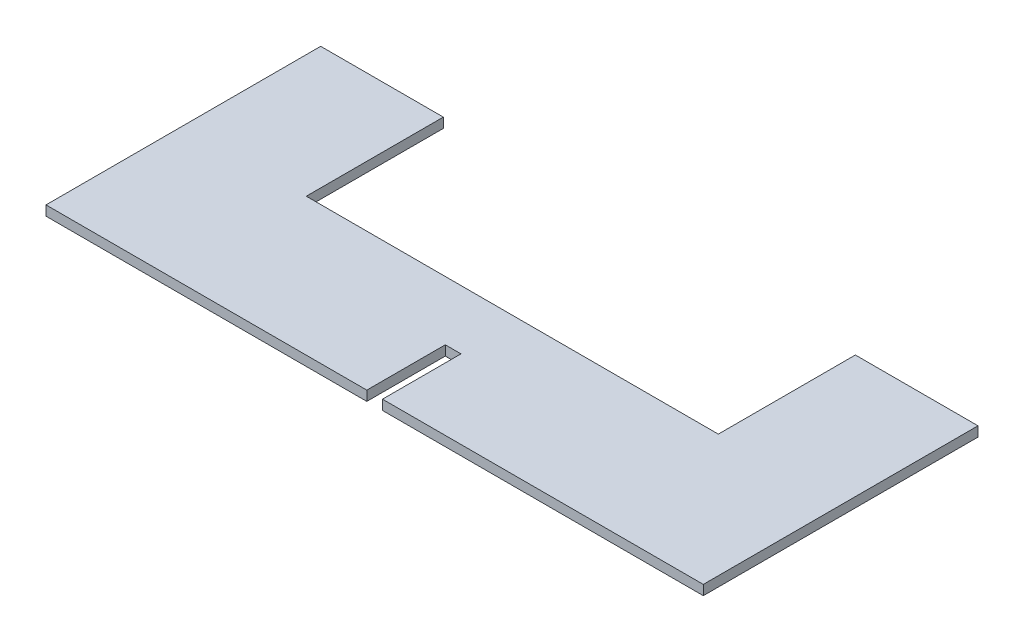
SolidWorks part; units mm, degrees
ref_plane "Alzado" through (0, 0, 0) normal (0, 0, 1) x (1, 0, 0)
ref_plane "Planta" through (0, 0, 0) normal (0, 1, 0) x (1, 0, 0)
ref_plane "Vista lateral" through (0, 0, 0) normal (1, 0, 0) x (0, 0, -1)
sketch "Croquis1" plane through (0, 0, 0) normal (0, 1, 0) x (1, 0, 0)
  line L0 (0, 0) -> (16.35, 0)
  line L1 (33.5, 0) -> (33.5, 14)
  line L2 (33.5, 14) -> (27.25, 14)
  line L3 (27.25, 14) -> (27.25, 7.0152)
  line L8 (27.25, 7.0152) -> (6.25, 7.0152)
  line L9 (6.25, 7.0152) -> (6.25, 14)
  line L10 (6.25, 14) -> (0, 14)
  line L11 (0, 14) -> (0, 0)
  line L12 (16.35, 0) -> (16.35, 4)
  line L13 (16.35, 4) -> (17.15, 4)
  line L14 (17.15, 4) -> (17.15, 0)
  line L15 (16.75, 4) -> (16.75, 7.0152) construction
  line L16 (17.15, 0) -> (33.5, 0)
  dimension "D1" = 14
  dimension "D2" = 4
  dimension "D3" = 0.8
  dimension "D5" = 21
  dimension "D6" = 33.5
extrude "Saliente-Extruir1" add sketch "Croquis1" along normal blind 0.5
